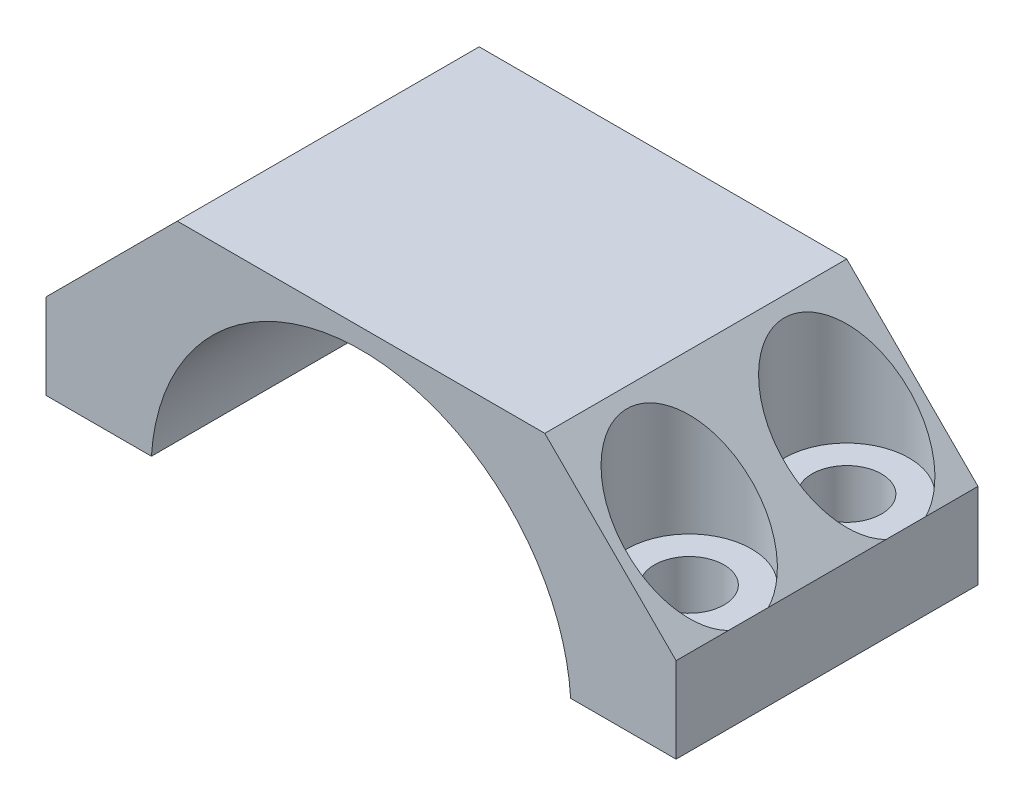
SolidWorks part; units mm, degrees
material "7075-T6 (SN)"
ref_plane "Front" through (0, 0, 0) normal (0, 0, 1) x (1, 0, 0)
ref_plane "Top" through (0, 0, 0) normal (0, 1, 0) x (1, 0, 0)
ref_plane "Right" through (0, 0, 0) normal (1, 0, 0) x (0, 0, -1)
sketch "Sketch1" plane through (0, 0, 0) normal (0, 0, 1) x (1, 0, 0)
  line L1 (-24, 17.5) -> (24, 17.5)
  line L2 (-24, 17.5) -> (-24, 0)
  line L3 (-24, 0) -> (24, 0)
  line L4 (24, 17.5) -> (24, 0)
  circle A0 centre (0, 0) radius 16
  point P7 (0, 0)
  dimension "D3" = 32
  dimension "D1" = 17.5
  dimension "D2" = 48
extrude "Boss-Extrude1" add sketch "Sketch1" along normal mid plane 23 contours A0 L3 L4 L1 L2
hole_wizard "CBORE for M5 SHCS1" positions "Sketch3" profile "Sketch2" counterbore size "M5" standard "ANSI Metric" end condition up to next
sketch "Sketch3" plane through (0, 17.5, 0) normal (0, 1, 0) x (1, 0, 0)
  line L0 (19.5, -6) -> (19.5, 6) construction
  line L3 (-19.5, -6) -> (-19.5, 6) construction
  line L6 (-19.5, 0) -> (19.5, 0) construction
  point P0 (-19.5, -6)
  point P2 (-19.5, 6)
  point P4 (19.5, -6)
  point P6 (19.5, 6)
  point P22 (0, 0)
  dimension "D1" = 39
  dimension "D2" = 12
sketch "Sketch2" plane through (-19.5, 17.5, 6) normal (1, 0, 0) x (0, 0, 1)
  line L0 (0, 0) -> (0, 17.5)
  line L1 (0, 17.5) -> (2.65, 17.5)
  line L3 (2.65, 17.5) -> (2.65, 10)
  line L4 (2.65, 10) -> (4.75, 10)
  line L5 (4.75, 10) -> (4.75, 0)
  line L7 (4.75, 0) -> (0, 0)
  line L11 (0, -6.35) -> (0, 107.95) construction
  dimension "Thru Hole Dia." = 5.3
  dimension "Thru Hole Depth" = 17.5
  dimension "C'Bore Dia." = 9.5
  dimension "C'Bore Depth" = 10
sketch "Sketch4" plane through (0, 0, 11.5) normal (0, 0, 1) x (1, 0, 0)
  line L0 (24, 17.5) -> (14, 17.5)
  line L1 (-24, 17.5) -> (24, 17.5) construction
  line L2 (14, 17.5) -> (24, 7.5)
  line L3 (24, 17.5) -> (24, 0) construction
  line L4 (24, 7.5) -> (24, 17.5)
  line L5 (-14, 17.5) -> (-24, 17.5)
  line L6 (-24, 17.5) -> (-24, 7.5)
  line L7 (-24, 17.5) -> (-24, 0) construction
  line L8 (-24, 7.5) -> (-14, 17.5)
  dimension "D1" = 10
extrude "Chamfer" cut sketch "Sketch4" against normal up to next
sketch "Sketch5" plane through (0, 0, 0) normal (0, -1, 0) x (-1, 0, 0)
  line L1 (24, -11.5) -> (-24, -11.5)
  line L2 (24, -11.5) -> (24, 11.5)
  line L3 (24, 11.5) -> (-24, 11.5)
  line L4 (-24, -11.5) -> (-24, 11.5)
extrude "Cut-Extrude2" cut sketch "Sketch5" against normal blind 1
